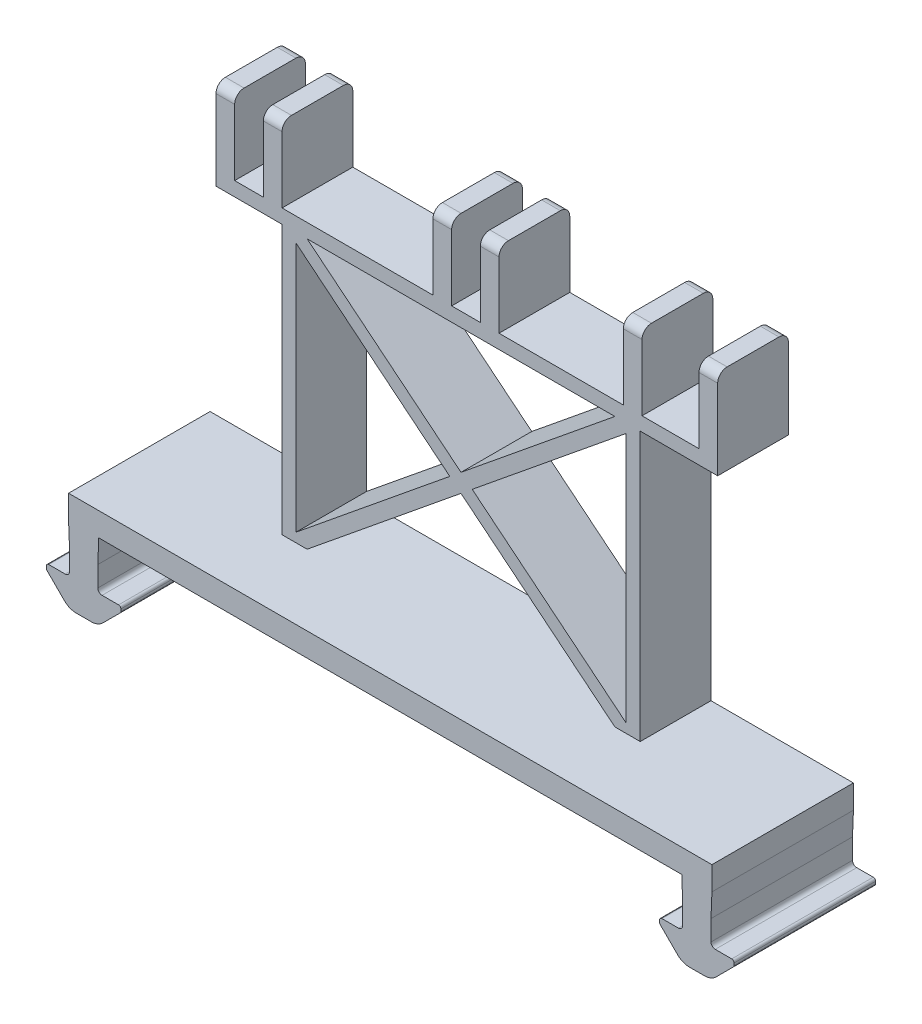
SolidWorks part; units mm, degrees
ref_plane "Front Plane" through (0, 0, 0) normal (0, 0, 1) x (1, 0, 0)
ref_plane "Top Plane" through (0, 0, 0) normal (0, 1, 0) x (1, 0, 0)
ref_plane "Right Plane" through (0, 0, 0) normal (1, 0, 0) x (0, 0, -1)
sketch "Sketch1" plane through (0, 0, 0) normal (0, 0, 1) x (1, 0, 0)
  line L7 (0, 0) -> (0, 26.663) construction
  line L8 (-2.0169, 6.858) -> (2.0169, 6.858)
  line L9 (5.3755, 8.2492) -> (10.0266, 12.9003)
  line L10 (10.287, 13.5289) -> (10.287, 14.0979)
  line L11 (9.398, 14.9869) -> (4.953, 14.9869)
  line L12 (4.064, 15.8759) -> (4.064, 27.6869)
  line L13 (0, 0) -> (20.2214, 20.2214) construction
  line L14 (-4.064, 15.8759) -> (-4.064, 27.6869)
  line L15 (-9.398, 14.9869) -> (-4.953, 14.9869)
  line L16 (-10.287, 13.5289) -> (-10.287, 14.0979)
  line L17 (-5.3755, 8.2492) -> (-10.0266, 12.9003)
  line L19 (163.0831, 6.858) -> (167.1169, 6.858)
  line L20 (170.4755, 8.2492) -> (175.1266, 12.9003)
  line L21 (175.387, 13.5289) -> (175.387, 14.0979)
  line L22 (174.498, 14.9869) -> (170.053, 14.9869)
  line L23 (169.164, 15.8759) -> (169.164, 27.6869)
  line L24 (161.036, 15.8759) -> (161.036, 27.6869)
  line L25 (155.702, 14.9869) -> (160.147, 14.9869)
  line L26 (154.813, 13.5289) -> (154.813, 14.0979)
  line L27 (159.7245, 8.2492) -> (155.0734, 12.9003)
  line L29 (-4.064, 27.6869) -> (-4.064, 34.0369)
  line L30 (-4.064, 34.0369) -> (169.164, 34.0369)
  line L31 (169.164, 34.0369) -> (169.164, 27.6869)
  line L32 (4.064, 27.6869) -> (161.036, 27.6869)
  arc A0 (10.0266, 12.9003) -> (10.287, 13.5289) centre (9.398, 13.5289) ccw
  arc A1 (9.398, 14.9869) -> (10.287, 14.0979) centre (9.398, 14.0979) cw
  arc A2 (4.953, 14.9869) -> (4.064, 15.8759) centre (4.953, 15.8759) cw
  arc A3 (2.0169, 6.858) -> (5.3755, 8.2492) centre (2.0169, 11.6078) ccw
  arc A4 (-2.0169, 6.858) -> (-5.3755, 8.2492) centre (-2.0169, 11.6078) cw
  arc A5 (-4.953, 14.9869) -> (-4.064, 15.8759) centre (-4.953, 15.8759) ccw
  arc A6 (-9.398, 14.9869) -> (-10.287, 14.0979) centre (-9.398, 14.0979) ccw
  arc A7 (-10.0266, 12.9003) -> (-10.287, 13.5289) centre (-9.398, 13.5289) cw
  arc A8 (175.1266, 12.9003) -> (175.387, 13.5289) centre (174.498, 13.5289) ccw
  arc A9 (174.498, 14.9869) -> (175.387, 14.0979) centre (174.498, 14.0979) cw
  arc A10 (170.053, 14.9869) -> (169.164, 15.8759) centre (170.053, 15.8759) cw
  arc A11 (167.1169, 6.858) -> (170.4755, 8.2492) centre (167.1169, 11.6078) ccw
  arc A12 (163.0831, 6.858) -> (159.7245, 8.2492) centre (163.0831, 11.6078) cw
  arc A13 (160.147, 14.9869) -> (161.036, 15.8759) centre (160.147, 15.8759) ccw
  arc A14 (155.702, 14.9869) -> (154.813, 14.0979) centre (155.702, 14.0979) ccw
  arc A15 (155.0734, 12.9003) -> (154.813, 13.5289) centre (155.702, 13.5289) cw
  point P1 (-4.064, 14.9869)
  point P20 (4.064, 14.9869)
  point P34 (0, 6.858)
  point P36 (161.036, 14.9869)
  point P63 (165.1, 6.858)
  dimension "D6" = 0.889
  dimension "D9" = 4.7498
  dimension "D1" = 12.7
  dimension "D2" = 4.064
  dimension "D3" = 6.858
  dimension "D4" = 10.287
  dimension "D5" = 2.032
  dimension "D7" = 0.569
  dimension "D8" = 45
  dimension "D11" = 165.1
  dimension "D12" = 6.35
  dimension "D10" = 2
extrude "Boss-Extrude2" add sketch "Sketch1" along normal blind 38.1
sketch "Sketch7" plane through (0, 0, 0) normal (0, 0, 1) x (1, 0, 0)
  line L0 (82.55, 68.2701) -> (82.55, 42.7511) construction
  line L1 (130.81, 106.4269) -> (169.164, 106.4269)
  line L3 (169.164, 34.0369) -> (-4.064, 34.0369) construction
  line L4 (-4.064, 34.0369) -> (-4.064, 15.8759) construction
  line L6 (34.29, 106.4269) -> (34.29, 34.0369)
  line L7 (34.29, 34.0369) -> (38.1, 34.0369)
  line L8 (130.81, 106.4269) -> (130.81, 34.0369)
  line L9 (-4.064, 110.2369) -> (169.164, 110.2369)
  line L10 (-4.064, 110.2369) -> (-4.064, 106.4269)
  line L11 (-4.064, 106.4269) -> (34.29, 106.4269)
  line L12 (169.164, 110.2369) -> (169.164, 106.4269)
  line L13 (38.1, 34.0369) -> (38.1, 106.4269)
  line L14 (127, 106.4269) -> (127, 34.0369)
  line L15 (38.1, 106.4269) -> (127, 106.4269)
  line L16 (127, 34.0369) -> (130.81, 34.0369)
  point P4 (82.55, 34.0369)
  point P15 (82.55, 110.2369)
  dimension "D1" = 72.39
  dimension "D2" = 3.81
  dimension "D3" = 3.81
  dimension "D4" = 44.45
extrude "Boss-Extrude6" add sketch "Sketch7" along normal blind 19.05
sketch "Sketch6" plane through (0, 110.2369, 0) normal (0, 1, 0) x (1, 0, 0)
  line L1 (16.576, 0) -> (21.656, 0)
  line L2 (16.576, 0) -> (16.576, -19.05)
  line L3 (16.576, -19.05) -> (21.656, -19.05)
  line L4 (21.656, 0) -> (21.656, -19.05)
  line L24 (169.164, 0) -> (130.81, 0) construction
  line L25 (29.2862, 0) -> (29.2862, -19.05)
  line L27 (29.2862, -19.05) -> (34.3662, -19.05)
  line L28 (34.3662, 0) -> (34.3662, -19.05)
  line L29 (29.2862, 0) -> (34.3662, 0)
  line L30 (75.0062, 0) -> (75.0062, -19.05)
  line L31 (75.0062, -19.05) -> (80.0862, -19.05)
  line L32 (80.0862, 0) -> (80.0862, -19.05)
  line L33 (75.0062, 0) -> (80.0862, 0)
  line L34 (87.7062, 0) -> (87.7062, -19.05)
  line L35 (87.7062, -19.05) -> (92.7862, -19.05)
  line L36 (92.7862, 0) -> (92.7862, -19.05)
  line L37 (87.7062, 0) -> (92.7862, 0)
  line L38 (126.2634, 0) -> (126.2634, -19.05)
  line L39 (126.2634, -19.05) -> (131.3434, -19.05)
  line L40 (131.3434, 0) -> (131.3434, -19.05)
  line L41 (126.2634, 0) -> (131.3434, 0)
  line L42 (146.5834, 0) -> (146.5834, -19.05)
  line L43 (146.5834, -19.05) -> (151.6634, -19.05)
  line L44 (151.6634, 0) -> (151.6634, -19.05)
  line L45 (146.5834, 0) -> (151.6634, 0)
  line L47 (169.164, -19.05) -> (169.164, 0) construction
  point P32 (87.7062, -9.525)
  point P33 (29.2862, -9.525)
  dimension "D1" = 5.08
  dimension "D2" = 19.05
  dimension "D4" = 58.8772
  dimension "D5" = 5.08
  dimension "D6" = 5.08
  dimension "D3" = 5.08
  dimension "D7" = 5.08
  dimension "D8" = 5.08
  dimension "D9" = 117.2972
  dimension "D12" = 17.5006
  dimension "D14" = 15.24
  dimension "D15" = 7.62
  dimension "D16" = 7.6302
extrude "Boss-Extrude5" add sketch "Sketch6" along normal blind 20.32
sketch "Sketch10" plane through (0, 0, 0) normal (0, 0, 1) x (1, 0, 0)
  line L1 (16.576, 110.2369) -> (-4.064, 110.2369)
  line L2 (16.576, 110.2369) -> (16.576, 106.4269)
  line L3 (16.576, 106.4269) -> (-4.064, 106.4269)
  line L4 (-4.064, 110.2369) -> (-4.064, 106.4269)
  line L5 (151.6634, 110.2369) -> (169.164, 110.2369)
  line L6 (151.6634, 110.2369) -> (151.6634, 106.4269)
  line L7 (151.6634, 106.4269) -> (169.164, 106.4269)
  line L8 (169.164, 110.2369) -> (169.164, 106.4269)
extrude "Cut-Extrude3" cut sketch "Sketch10" along normal up to surface (19.05 mm away) up to face at (82.7013, 107.9085, 19.05)
fillet "Fillet1" radius 2.54 12 edges at (149.1234, 130.5569, 0) (128.8034, 130.5569, 0) (149.1234, 130.5569, 19.05) (128.8034, 130.5569, 19.05) (90.2462, 130.5569, 0) (90.2462, 130.5569, 19.05) (77.5462, 130.5569, 19.05) (77.5462, 130.5569, 0) (31.8262, 130.5569, 0) (19.116, 130.5569, 0) (19.116, 130.5569, 19.05) (31.8262, 130.5569, 19.05)
sketch "Sketch11" plane through (0, 0, 0) normal (0, 0, 1) x (1, 0, 0)
  line L0 (38.1, 103.9702) -> (79.533, 70.2319)
  line L1 (38.1, 34.0369) -> (38.1, 106.4269) construction
  line L2 (169.164, 34.0369) -> (-4.064, 34.0369) construction
  line L3 (123.983, 34.0369) -> (127, 34.0369)
  line L4 (127, 34.0369) -> (127, 36.4936)
  line L5 (127, 106.4269) -> (127, 34.0369) construction
  line L6 (127, 36.4936) -> (85.567, 70.2319)
  line L7 (38.1, 106.4269) -> (127, 106.4269) construction
  line L8 (41.117, 106.4269) -> (38.1, 106.4269)
  line L9 (38.1, 106.4269) -> (38.1, 103.9702)
  line L10 (123.983, 106.4269) -> (127, 106.4269)
  line L11 (127, 106.4269) -> (127, 103.9702)
  line L12 (127, 103.9702) -> (85.567, 70.2319)
  line L13 (41.117, 34.0369) -> (38.1, 34.0369)
  line L14 (38.1, 34.0369) -> (38.1, 36.4936)
  line L15 (38.1, 36.4936) -> (79.533, 70.2319)
  line L16 (38.1, 34.0369) -> (127, 106.4269) construction
  line L17 (38.1, 106.4269) -> (127, 34.0369) construction
  line L18 (82.55, 67.7752) -> (41.117, 34.0369)
  line L19 (82.55, 67.7752) -> (123.983, 34.0369)
  line L20 (82.55, 72.6886) -> (123.983, 106.4269)
  line L21 (82.55, 72.6886) -> (41.117, 106.4269)
  dimension "D1" = 3.81
  dimension "D2" = 3.81
extrude "Boss-Extrude7" add sketch "Sketch11" along normal up to surface (19.05 mm away) up to face at (82.7202, 106.665, 19.05)
sketch "Sketch3" plane through (0, 0, 38.1) normal (0, 0, 1) x (1, 0, 0)
  line L27 (-3.937, 21.3369) -> (3.937, 21.3369) construction
  line L28 (4.064, 27.6869) -> (3.81, 21.3369)
  line L29 (-4.064, 27.6869) -> (-3.81, 21.3369)
  line L40 (-4.064, 34.0369) -> (-4.064, 15.8759) construction
  line L41 (-1004.064, 27.6869) -> (4.064, 27.6869) construction
  line L42 (161.036, 27.6869) -> (161.29, 21.3369)
  line L43 (169.164, 27.6869) -> (168.91, 21.3369)
  line L44 (169.164, 15.8759) -> (169.164, 34.0369) construction
  line L57 (5.1959, 8.4288) -> (9.847, 13.0799)
  line L58 (10.033, 13.5289) -> (10.033, 14.0979)
  line L59 (9.398, 14.7329) -> (4.953, 14.7329)
  line L61 (3.81, 15.8759) -> (3.81, 27.9409)
  line L62 (3.81, 27.9409) -> (161.29, 27.9409)
  line L66 (161.29, 27.9409) -> (161.29, 15.8759)
  line L67 (160.147, 14.7329) -> (155.702, 14.7329)
  line L68 (155.067, 14.0979) -> (155.067, 13.5289)
  line L69 (155.253, 13.0799) -> (159.9041, 8.4288)
  line L80 (163.0831, 7.112) -> (167.1169, 7.112)
  line L81 (170.2959, 8.4288) -> (174.947, 13.0799)
  line L82 (175.133, 13.5289) -> (175.133, 14.0979)
  line L85 (174.498, 14.7329) -> (170.053, 14.7329)
  line L86 (168.91, 15.8759) -> (168.91, 33.7829)
  line L91 (168.91, 33.7829) -> (-3.81, 33.7829)
  line L93 (-3.81, 33.7829) -> (-3.81, 15.8759)
  line L95 (-4.953, 14.7329) -> (-9.398, 14.7329)
  line L97 (-10.033, 14.0979) -> (-10.033, 13.5289)
  line L99 (-9.847, 13.0799) -> (-5.1959, 8.4288)
  line L101 (-2.0169, 7.112) -> (2.0169, 7.112)
  line L103 (5.1959, 8.4288) -> (9.847, 13.0799)
  line L105 (10.033, 13.5289) -> (10.033, 14.0979)
  line L109 (9.398, 14.7329) -> (4.953, 14.7329)
  line L110 (3.81, 15.8759) -> (3.81, 21.3369)
  line L112 (161.29, 21.3369) -> (161.29, 15.8759)
  line L113 (160.147, 14.7329) -> (155.702, 14.7329)
  line L114 (155.067, 14.0979) -> (155.067, 13.5289)
  line L115 (155.253, 13.0799) -> (159.9041, 8.4288)
  line L116 (163.0831, 7.112) -> (167.1169, 7.112)
  line L117 (170.2959, 8.4288) -> (174.947, 13.0799)
  line L118 (175.133, 13.5289) -> (175.133, 14.0979)
  line L119 (174.498, 14.7329) -> (170.053, 14.7329)
  line L120 (168.91, 15.8759) -> (168.91, 21.3369)
  line L122 (-3.81, 21.3369) -> (-3.81, 15.8759)
  line L123 (-4.953, 14.7329) -> (-9.398, 14.7329)
  line L124 (-10.033, 14.0979) -> (-10.033, 13.5289)
  line L125 (-9.847, 13.0799) -> (-5.1959, 8.4288)
  line L126 (-2.0169, 7.112) -> (2.0169, 7.112)
  line L137 (161.036, 27.6869) -> (1318.008, 27.6869) construction
  line L138 (16.576, 130.5569) -> (21.656, 130.5569) construction
  line L139 (21.6052, 130.5569) -> (29.337, 130.5569)
  line L140 (21.6052, 130.5569) -> (21.6052, 110.2369)
  line L141 (21.6052, 110.2369) -> (29.337, 110.2369)
  line L142 (29.337, 130.5569) -> (29.337, 110.2369)
  line L143 (126.2634, 130.5569) -> (131.3434, 130.5569) construction
  line L144 (80.0354, 130.5569) -> (87.757, 130.5569)
  line L145 (80.0354, 130.5569) -> (80.0354, 110.2369)
  line L146 (80.0354, 110.2369) -> (87.757, 110.2369)
  line L147 (87.757, 130.5569) -> (87.757, 110.2369)
  line L148 (131.2926, 130.5569) -> (146.6342, 130.5569)
  line L149 (131.2926, 130.5569) -> (131.2926, 110.2369)
  line L150 (131.2926, 110.2369) -> (146.6342, 110.2369)
  line L151 (146.6342, 130.5569) -> (146.6342, 110.2369)
  line L152 (126.2634, 110.2369) -> (92.7862, 110.2369) construction
  line L153 (21.656, 128.0169) -> (21.656, 110.2369) construction
  line L154 (29.2862, 128.0169) -> (29.2862, 110.2369) construction
  line L155 (80.0862, 128.0169) -> (80.0862, 110.2369) construction
  line L156 (87.7062, 128.0169) -> (87.7062, 110.2369) construction
  line L157 (5.3755, 8.2492) -> (10.0266, 12.9003)
  line L158 (10.287, 13.5289) -> (10.287, 14.0979)
  line L159 (9.398, 14.9869) -> (4.953, 14.9869)
  line L160 (4.064, 15.8759) -> (4.064, 27.6869)
  line L161 (4.064, 27.6869) -> (161.036, 27.6869)
  line L162 (161.036, 27.6869) -> (161.036, 15.8759)
  line L163 (160.147, 14.9869) -> (155.702, 14.9869)
  line L164 (154.813, 14.0979) -> (154.813, 13.5289)
  line L165 (155.0734, 12.9003) -> (159.7245, 8.2492)
  line L166 (163.0831, 6.858) -> (167.1169, 6.858)
  line L167 (170.4755, 8.2492) -> (175.1266, 12.9003)
  line L168 (175.387, 13.5289) -> (175.387, 14.0979)
  line L169 (174.498, 14.9869) -> (170.053, 14.9869)
  line L170 (169.164, 15.8759) -> (169.164, 34.0369)
  line L171 (169.164, 34.0369) -> (-4.064, 34.0369)
  line L172 (-4.064, 34.0369) -> (-4.064, 15.8759)
  line L173 (-4.953, 14.9869) -> (-9.398, 14.9869)
  line L174 (-10.287, 14.0979) -> (-10.287, 13.5289)
  line L175 (-10.0266, 12.9003) -> (-5.3755, 8.2492)
  line L176 (-2.0169, 6.858) -> (2.0169, 6.858)
  line L177 (5.3755, 8.2492) -> (10.0266, 12.9003)
  line L178 (10.287, 13.5289) -> (10.287, 14.0979)
  line L179 (9.398, 14.9869) -> (4.953, 14.9869)
  line L180 (4.064, 15.8759) -> (4.064, 27.6869)
  line L182 (161.036, 27.6869) -> (161.036, 15.8759)
  line L183 (160.147, 14.9869) -> (155.702, 14.9869)
  line L184 (154.813, 14.0979) -> (154.813, 13.5289)
  line L185 (155.0734, 12.9003) -> (159.7245, 8.2492)
  line L186 (163.0831, 6.858) -> (167.1169, 6.858)
  line L187 (170.4755, 8.2492) -> (175.1266, 12.9003)
  line L188 (175.387, 13.5289) -> (175.387, 14.0979)
  line L189 (174.498, 14.9869) -> (170.053, 14.9869)
  line L190 (169.164, 15.8759) -> (169.164, 27.6869)
  line L192 (-4.064, 27.6869) -> (-4.064, 15.8759)
  line L193 (-4.953, 14.9869) -> (-9.398, 14.9869)
  line L194 (-10.287, 14.0979) -> (-10.287, 13.5289)
  line L195 (-10.0266, 12.9003) -> (-5.3755, 8.2492)
  line L196 (-2.0169, 6.858) -> (2.0169, 6.858)
  line L197 (87.7062, 130.5569) -> (92.7862, 130.5569) construction
  line L198 (131.3434, 128.0169) -> (131.3434, 110.2369) construction
  line L199 (146.5834, 128.0169) -> (146.5834, 110.2369) construction
  arc A96 (2.0169, 7.112) -> (5.1959, 8.4288) centre (2.0169, 11.6078) ccw
  arc A97 (9.847, 13.0799) -> (10.033, 13.5289) centre (9.398, 13.5289) ccw
  arc A98 (10.033, 14.0979) -> (9.398, 14.7329) centre (9.398, 14.0979) ccw
  arc A99 (3.81, 15.8759) -> (4.953, 14.7329) centre (4.953, 15.8759) ccw
  arc A100 (160.147, 14.7329) -> (161.29, 15.8759) centre (160.147, 15.8759) ccw
  arc A101 (155.702, 14.7329) -> (155.067, 14.0979) centre (155.702, 14.0979) ccw
  arc A102 (155.067, 13.5289) -> (155.253, 13.0799) centre (155.702, 13.5289) ccw
  arc A103 (159.9041, 8.4288) -> (163.0831, 7.112) centre (163.0831, 11.6078) ccw
  arc A104 (167.1169, 7.112) -> (170.2959, 8.4288) centre (167.1169, 11.6078) ccw
  arc A105 (174.947, 13.0799) -> (175.133, 13.5289) centre (174.498, 13.5289) ccw
  arc A106 (175.133, 14.0979) -> (174.498, 14.7329) centre (174.498, 14.0979) ccw
  arc A107 (168.91, 15.8759) -> (170.053, 14.7329) centre (170.053, 15.8759) ccw
  arc A108 (-4.953, 14.7329) -> (-3.81, 15.8759) centre (-4.953, 15.8759) ccw
  arc A109 (-9.398, 14.7329) -> (-10.033, 14.0979) centre (-9.398, 14.0979) ccw
  arc A110 (-10.033, 13.5289) -> (-9.847, 13.0799) centre (-9.398, 13.5289) ccw
  arc A111 (-5.1959, 8.4288) -> (-2.0169, 7.112) centre (-2.0169, 11.6078) ccw
  arc A112 (2.0169, 7.112) -> (5.1959, 8.4288) centre (2.0169, 11.6078) ccw
  arc A113 (9.847, 13.0799) -> (10.033, 13.5289) centre (9.398, 13.5289) ccw
  arc A114 (10.033, 14.0979) -> (9.398, 14.7329) centre (9.398, 14.0979) ccw
  arc A115 (3.81, 15.8759) -> (4.953, 14.7329) centre (4.953, 15.8759) ccw
  arc A116 (160.147, 14.7329) -> (161.29, 15.8759) centre (160.147, 15.8759) ccw
  arc A117 (155.702, 14.7329) -> (155.067, 14.0979) centre (155.702, 14.0979) ccw
  arc A118 (155.067, 13.5289) -> (155.253, 13.0799) centre (155.702, 13.5289) ccw
  arc A119 (159.9041, 8.4288) -> (163.0831, 7.112) centre (163.0831, 11.6078) ccw
  arc A120 (167.1169, 7.112) -> (170.2959, 8.4288) centre (167.1169, 11.6078) ccw
  arc A121 (174.947, 13.0799) -> (175.133, 13.5289) centre (174.498, 13.5289) ccw
  arc A122 (175.133, 14.0979) -> (174.498, 14.7329) centre (174.498, 14.0979) ccw
  arc A123 (168.91, 15.8759) -> (170.053, 14.7329) centre (170.053, 15.8759) ccw
  arc A124 (-4.953, 14.7329) -> (-3.81, 15.8759) centre (-4.953, 15.8759) ccw
  arc A125 (-9.398, 14.7329) -> (-10.033, 14.0979) centre (-9.398, 14.0979) ccw
  arc A126 (-10.033, 13.5289) -> (-9.847, 13.0799) centre (-9.398, 13.5289) ccw
  arc A127 (-5.1959, 8.4288) -> (-2.0169, 7.112) centre (-2.0169, 11.6078) ccw
  arc A144 (2.0169, 6.858) -> (5.3755, 8.2492) centre (2.0169, 11.6078) ccw
  arc A145 (10.0266, 12.9003) -> (10.287, 13.5289) centre (9.398, 13.5289) ccw
  arc A146 (10.287, 14.0979) -> (9.398, 14.9869) centre (9.398, 14.0979) ccw
  arc A147 (4.064, 15.8759) -> (4.953, 14.9869) centre (4.953, 15.8759) ccw
  arc A148 (160.147, 14.9869) -> (161.036, 15.8759) centre (160.147, 15.8759) ccw
  arc A149 (155.702, 14.9869) -> (154.813, 14.0979) centre (155.702, 14.0979) ccw
  arc A150 (154.813, 13.5289) -> (155.0734, 12.9003) centre (155.702, 13.5289) ccw
  arc A151 (159.7245, 8.2492) -> (163.0831, 6.858) centre (163.0831, 11.6078) ccw
  arc A152 (167.1169, 6.858) -> (170.4755, 8.2492) centre (167.1169, 11.6078) ccw
  arc A153 (175.1266, 12.9003) -> (175.387, 13.5289) centre (174.498, 13.5289) ccw
  arc A154 (175.387, 14.0979) -> (174.498, 14.9869) centre (174.498, 14.0979) ccw
  arc A155 (169.164, 15.8759) -> (170.053, 14.9869) centre (170.053, 15.8759) ccw
  arc A156 (-4.953, 14.9869) -> (-4.064, 15.8759) centre (-4.953, 15.8759) ccw
  arc A157 (-9.398, 14.9869) -> (-10.287, 14.0979) centre (-9.398, 14.0979) ccw
  arc A158 (-10.287, 13.5289) -> (-10.0266, 12.9003) centre (-9.398, 13.5289) ccw
  arc A159 (-5.3755, 8.2492) -> (-2.0169, 6.858) centre (-2.0169, 11.6078) ccw
  arc A160 (2.0169, 6.858) -> (5.3755, 8.2492) centre (2.0169, 11.6078) ccw
  arc A161 (10.0266, 12.9003) -> (10.287, 13.5289) centre (9.398, 13.5289) ccw
  arc A162 (10.287, 14.0979) -> (9.398, 14.9869) centre (9.398, 14.0979) ccw
  arc A163 (4.064, 15.8759) -> (4.953, 14.9869) centre (4.953, 15.8759) ccw
  arc A164 (160.147, 14.9869) -> (161.036, 15.8759) centre (160.147, 15.8759) ccw
  arc A165 (155.702, 14.9869) -> (154.813, 14.0979) centre (155.702, 14.0979) ccw
  arc A166 (154.813, 13.5289) -> (155.0734, 12.9003) centre (155.702, 13.5289) ccw
  arc A167 (159.7245, 8.2492) -> (163.0831, 6.858) centre (163.0831, 11.6078) ccw
  arc A168 (167.1169, 6.858) -> (170.4755, 8.2492) centre (167.1169, 11.6078) ccw
  arc A169 (175.1266, 12.9003) -> (175.387, 13.5289) centre (174.498, 13.5289) ccw
  arc A170 (175.387, 14.0979) -> (174.498, 14.9869) centre (174.498, 14.0979) ccw
  arc A171 (169.164, 15.8759) -> (170.053, 14.9869) centre (170.053, 15.8759) ccw
  arc A172 (-4.953, 14.9869) -> (-4.064, 15.8759) centre (-4.953, 15.8759) ccw
  arc A173 (-9.398, 14.9869) -> (-10.287, 14.0979) centre (-9.398, 14.0979) ccw
  arc A174 (-10.287, 13.5289) -> (-10.0266, 12.9003) centre (-9.398, 13.5289) ccw
  arc A175 (-5.3755, 8.2492) -> (-2.0169, 6.858) centre (-2.0169, 11.6078) ccw
  dimension "D3" = 0
  dimension "D2" = 6.35
  dimension "D4" = 0.0508
  dimension "D5" = 0.0508
  dimension "D6" = 0.0508
  dimension "D7" = 0.0508
  dimension "D8" = 0.0508
  dimension "D9" = 0.0508
  dimension "D1" = 0.254
extrude "Clearance Trim" cut sketch "Sketch3" against normal up to surface (38.1 mm away)
